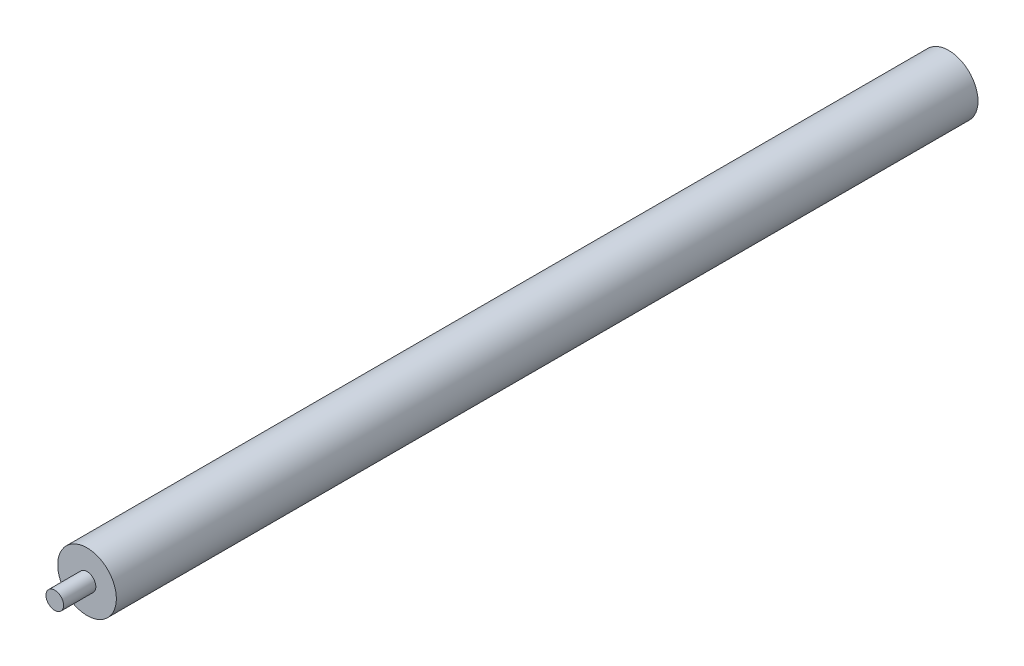
SolidWorks part; units mm, degrees
material "1060 Alloy"
ref_plane "Front Plane" through (0, 0, 0) normal (0, 0, 1) x (1, 0, 0)
ref_plane "Top Plane" through (0, 0, 0) normal (0, 1, 0) x (1, 0, 0)
ref_plane "Right Plane" through (0, 0, 0) normal (1, 0, 0) x (0, 0, -1)
sketch "Sketch2" plane through (0, 0, 0) normal (0, 1, 0) x (1, 0, 0)
  line L0 (0, 0) -> (3, 0)
  line L1 (3, 0) -> (3, 11)
  line L2 (0, 0) -> (0, 304.8)
  line L3 (3, 11) -> (10, 11)
  line L4 (10, 11) -> (10, 304.8)
  line L5 (10, 304.8) -> (0, 304.8)
  dimension "D1" = 3
  dimension "D2" = 11
  dimension "D3" = 7
  dimension "D4" = 304.8
revolve "Revolve1" add sketch "Sketch2" angle 360 about L2
